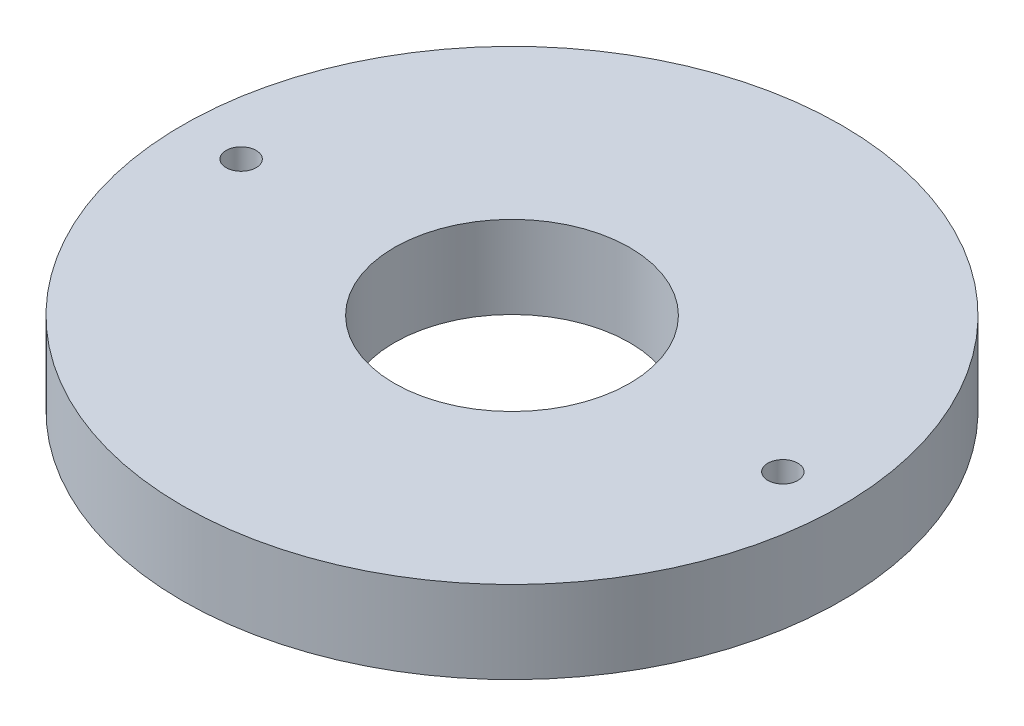
SolidWorks part; units mm, degrees
ref_plane "Front Plane" through (0, 0, 0) normal (0, 0, 1) x (1, 0, 0)
ref_plane "Top Plane" through (0, 0, 0) normal (0, 1, 0) x (1, 0, 0)
ref_plane "Right Plane" through (0, 0, 0) normal (1, 0, 0) x (0, 0, -1)
sketch "Sketch1" plane through (0, 0, 0) normal (0, 1, 0) x (1, 0, 0)
  circle A0 centre (0, 0) radius 28
  dimension "D1" = 56
extrude "Boss-Extrude1" add sketch "Sketch1" along normal blind 7
sketch "Sketch2" plane through (0, 0, 0) normal (0, 1, 0) x (1, 0, 0)
  circle A0 centre (0, 0) radius 10
extrude "Cut-Extrude1" cut sketch "Sketch2" along normal through all
sketch "Sketch3" plane through (0, 0, 0) normal (0, 1, 0) x (1, 0, 0)
  circle A0 centre (23.0124, 0) radius 1.275
  dimension "D1" = 23.0124
extrude "Cut-Extrude2" cut sketch "Sketch3" along normal through all
pattern_circular "CirPattern1" count 2 over 360 about axis through (0, 0, 0) along (0, 1, 0) of "Cut-Extrude2"
